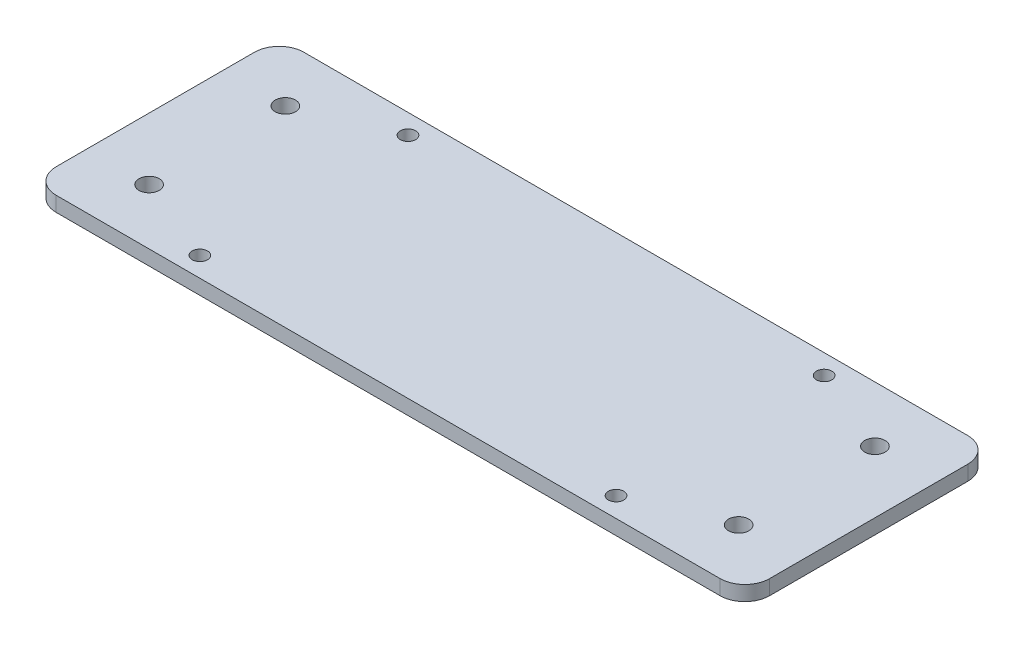
SolidWorks part; units mm, degrees
material "Thornel Mat VMA"
ref_plane "Front Plane" through (0, 0, 0) normal (0, 0, 1) x (1, 0, 0)
ref_plane "Top Plane" through (0, 0, 0) normal (0, 1, 0) x (1, 0, 0)
ref_plane "Right Plane" through (0, 0, 0) normal (1, 0, 0) x (0, 0, -1)
sketch "Sketch1" plane through (0, 0, 0) normal (0, 1, 0) x (1, 0, 0)
  line L0 (0, 0) -> (0, 61.7561) construction
  line L1 (0, 0) -> (91.8049, 0) construction
  line L2 (-72, 25) -> (72, 25)
  line L3 (72, 25) -> (72, -25)
  line L4 (-72, 25) -> (-72, -25)
  line L5 (-72, -25) -> (72, -25)
  circle A0 centre (59.5, 13.75) radius 2.05
  circle A1 centre (42, 21) radius 1.55
  circle A2 centre (-42, 21) radius 1.55
  circle A3 centre (-59.5, 13.75) radius 2.05
  circle A4 centre (-59.5, -13.75) radius 2.05
  circle A5 centre (-42, -21) radius 1.55
  circle A6 centre (42, -21) radius 1.55
  circle A7 centre (59.5, -13.75) radius 2.05
  point P17 (0, 25)
  point P26 (-72, 0)
  point P27 (72, 0)
  dimension "D2" = 3.1
  dimension "D3" = 4.1
  dimension "D4" = 21
  dimension "D5" = 42
  dimension "D6" = 12.5
  dimension "D7" = 13.75
  dimension "D1" = 72
  dimension "D8" = 25
extrude "Boss-Extrude1" add sketch "Sketch1" along normal blind 3
fillet "Fillet1" radius 5 4 edges at (-72, 1.5, -25) (72, 1.5, -25) (72, 1.5, 25) (-72, 1.5, 25)
